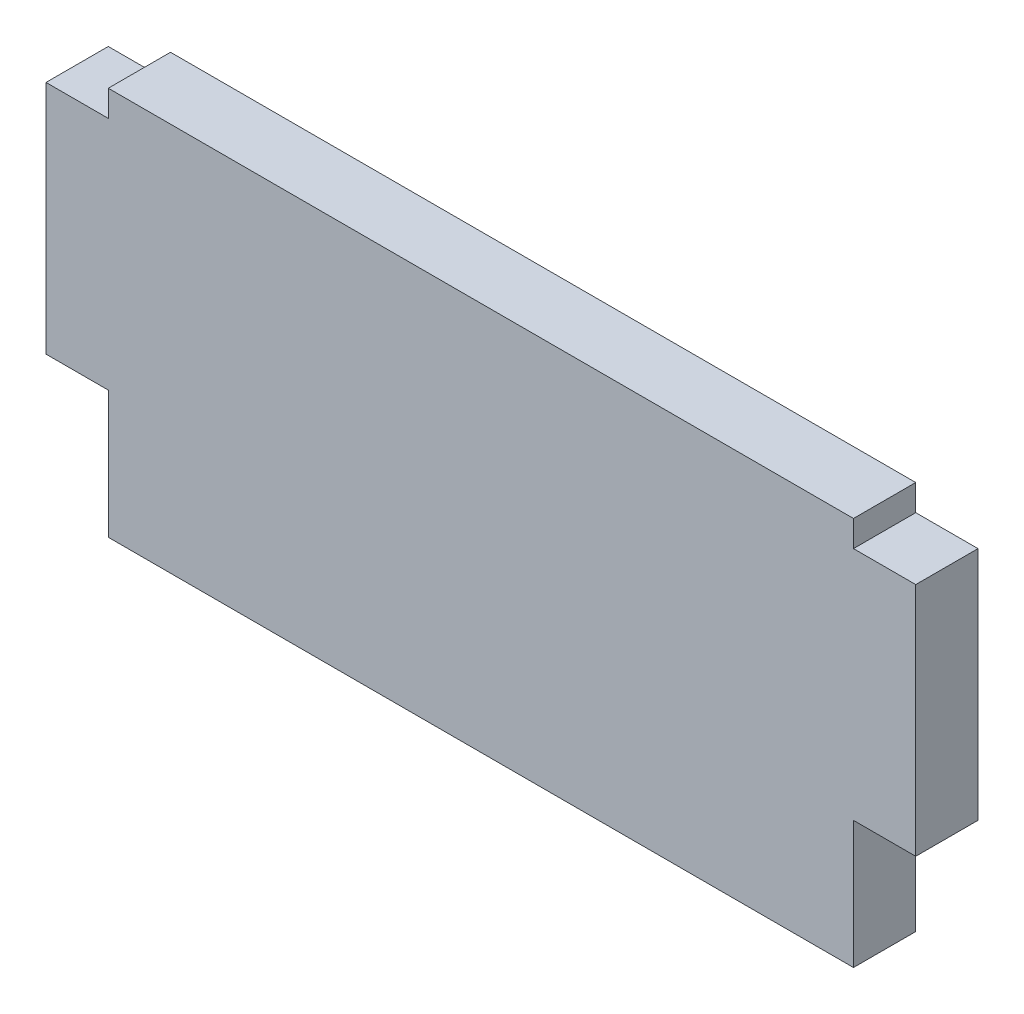
SolidWorks part; units mm, degrees
ref_plane "Front Plane" through (0, 0, 0) normal (0, 0, 1) x (1, 0, 0)
ref_plane "Top Plane" through (0, 0, 0) normal (0, 1, 0) x (1, 0, 0)
ref_plane "Right Plane" through (0, 0, 0) normal (1, 0, 0) x (0, 0, -1)
sketch "Sketch1" plane through (0, 0, 0) normal (0, 0, 1) x (1, 0, 0)
  line L0 (-19, 12.5) -> (19, 5.3317)
  line L1 (-19, -12.5) -> (19, -12.5)
  line L2 (-19, -12.5) -> (-19, 12.5)
  line L3 (-19, 12.5) -> (19, 12.5)
  line L4 (19, -12.5) -> (19, 12.5)
  line L5 (-19, -12.5) -> (19, 12.5) construction
  line L6 (-19, 12.5) -> (19, -12.5) construction
  line L7 (-19, -8) -> (-22.175, -8)
  line L8 (-19, -8) -> (-19, 10)
  line L9 (-19, 10) -> (-22.175, 10)
  line L10 (-22.175, -8) -> (-22.175, 10)
  line L11 (19, -8) -> (22.175, -8)
  line L12 (19, -8) -> (19, 4)
  line L13 (19, 4) -> (22.175, 4)
  line L14 (22.175, -8) -> (22.175, 4)
  point P0 (0, 0)
  dimension "D1" = 3.175
  dimension "D2" = 3.175
  dimension "D3" = 4.5
  dimension "D4" = 4.5
  dimension "D5" = 25
  dimension "D6" = 18
  dimension "D7" = 12
  dimension "D8" = 38
extrude "Boss-Extrude1" add sketch "Sketch1" along normal blind 3.175 contours L1 L4 L0 L2 | L11 L14 L13 L4 | L10 L7 L2 L9
sketch "Sketch2" plane through (0, 0, 3.175) normal (0, 0, 1) x (1, 0, 0)
  line L1 (19, -12.5) -> (-13.65, -12.5)
  line L2 (19, -12.5) -> (19, -14.5)
  line L3 (19, -14.5) -> (-13.65, -14.5)
  line L4 (-13.65, -12.5) -> (-13.65, -14.5)
  dimension "D1" = 32.65
  dimension "D2" = 2
extrude "Boss-Extrude2" add sketch "Sketch2" against normal up to surface (3.175 mm away) up to face at (0, -0.9307, 0)
sketch "Sketch3" plane through (0, 0, 3.175) normal (0, 0, 1) x (1, 0, 0)
  line L0 (-19, 9.8536) -> (-19, 4)
  line L1 (19, 5.3317) -> (-19, 5.3317)
  line L2 (19, 5.3317) -> (19, 12.5)
  line L3 (19, 12.5) -> (-19, 12.5)
  line L4 (-19, 5.3317) -> (-19, 12.5)
  line L5 (19, 4) -> (-25.3188, 4)
  line L6 (19, 4) -> (19, 11.1462)
  line L7 (19, 11.1462) -> (-25.3188, 11.1462)
  line L8 (-25.3188, 4) -> (-25.3188, 11.1462)
  line L9 (-19, 4) -> (-22.175, 4)
  line L10 (-22.175, -8) -> (-22.175, 10) construction
  line L11 (-19, 5.3317) -> (-22.175, 5.3317)
  line M9 (19, 5.3317) -> (-19, 12.5)
  line M10 (-19, 12.5) -> (-19, 10)
  line M11 (-19, 10) -> (-22.175, 10)
  line M12 (-22.175, 10) -> (-22.175, -8)
extrude "Cut-Extrude2" cut sketch "Sketch3" against normal blind 10 contours L0 L11 L5 M12 | L11 L0 L4 M11 M12 | L7 L4 L0 L1 M9 | L7 M9 M10
sketch "Sketch5" plane through (0, 0, 3.175) normal (0, 0, 1) x (1, 0, 0)
  line L0 (-19, -10.25) -> (-19, -14.5)
  line L2 (-19.825, -14.5) -> (-11.0247, -14.5)
  line L3 (-19.825, -14.5) -> (-19.825, -10.3974)
  line L4 (-13.65, -12.5) -> (-19.825, -12.5)
  line L5 (-13.65, -12.5) -> (-13.65, -14.5)
  line L6 (-13.65, -14.5) -> (-19.825, -14.5)
  line L7 (-19.825, -12.5) -> (-19.825, -14.5)
  line L8 (-19.825, -10.3974) -> (-11.0247, -10.3974)
  line L9 (-11.0247, -14.5) -> (-11.0247, -10.3974)
  line L10 (-19, -12.5) -> (-19, -8) construction
  line M9 (-19, -8) -> (-19, -12.5)
  line M10 (-19, -12.5) -> (-13.65, -12.5)
  line M11 (-13.65, -12.5) -> (-13.65, -14.5)
  line M12 (-13.65, -14.5) -> (19, -14.5)
extrude "Boss-Extrude5" add sketch "Sketch5" against normal up to surface (3.175 mm away) contours L9 L8 M12 M9 M10 M11 | L3 L2 M11 M10
